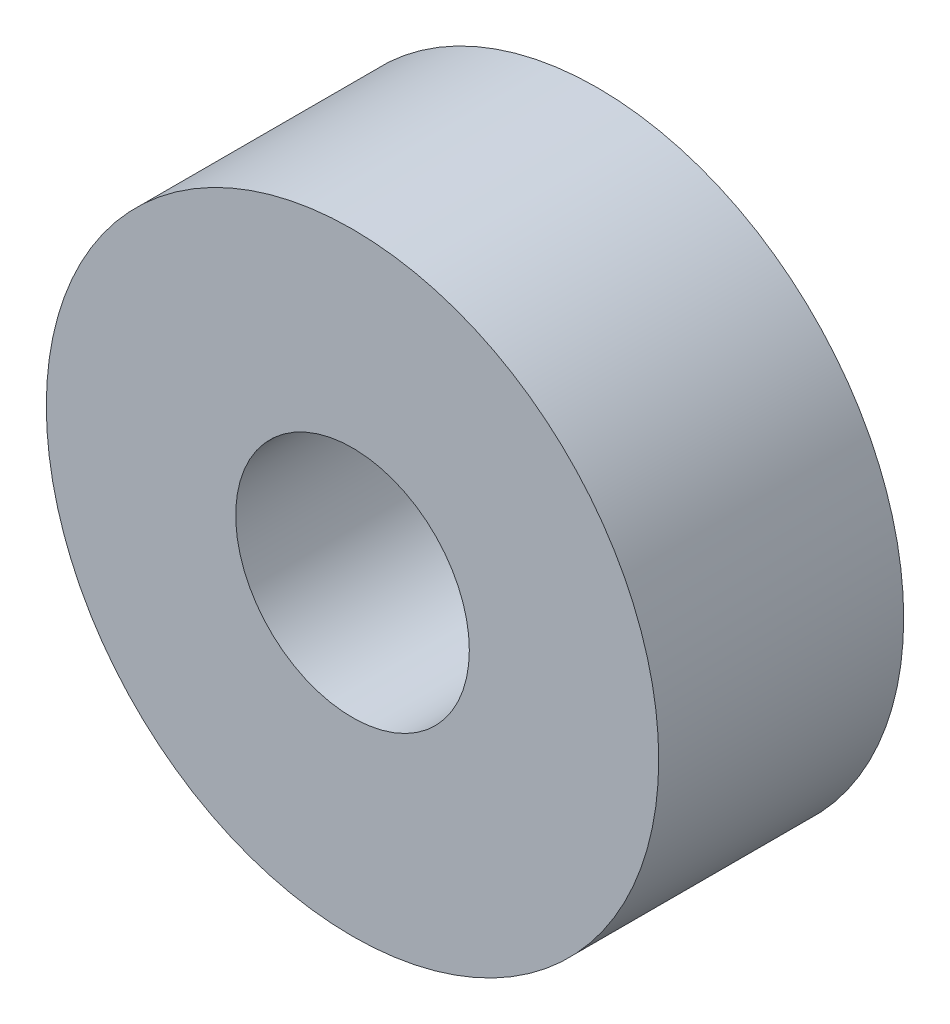
SolidWorks part; units mm, degrees
ref_plane "Plano frontal" through (0, 0, 0) normal (0, 0, 1) x (1, 0, 0)
ref_plane "Plano superior" through (0, 0, 0) normal (0, 1, 0) x (1, 0, 0)
ref_plane "Plano direito" through (0, 0, 0) normal (1, 0, 0) x (0, 0, -1)
sketch "Esboço1" plane through (0, 0, 0) normal (0, 0, 1) x (1, 0, 0)
  circle A0 centre (0, 0) radius 10
  dimension "D1" = 20
extrude "Ressalto-extrusão1" add sketch "Esboço1" along normal blind 8
sketch "Esboço2" plane through (0, 0, 8) normal (0, 0, 1) x (1, 0, 0)
  circle A0 centre (0, 0) radius 3.815
  dimension "D1" = 7.63
extrude "Corte-extrusão1" cut sketch "Esboço2" against normal through all
